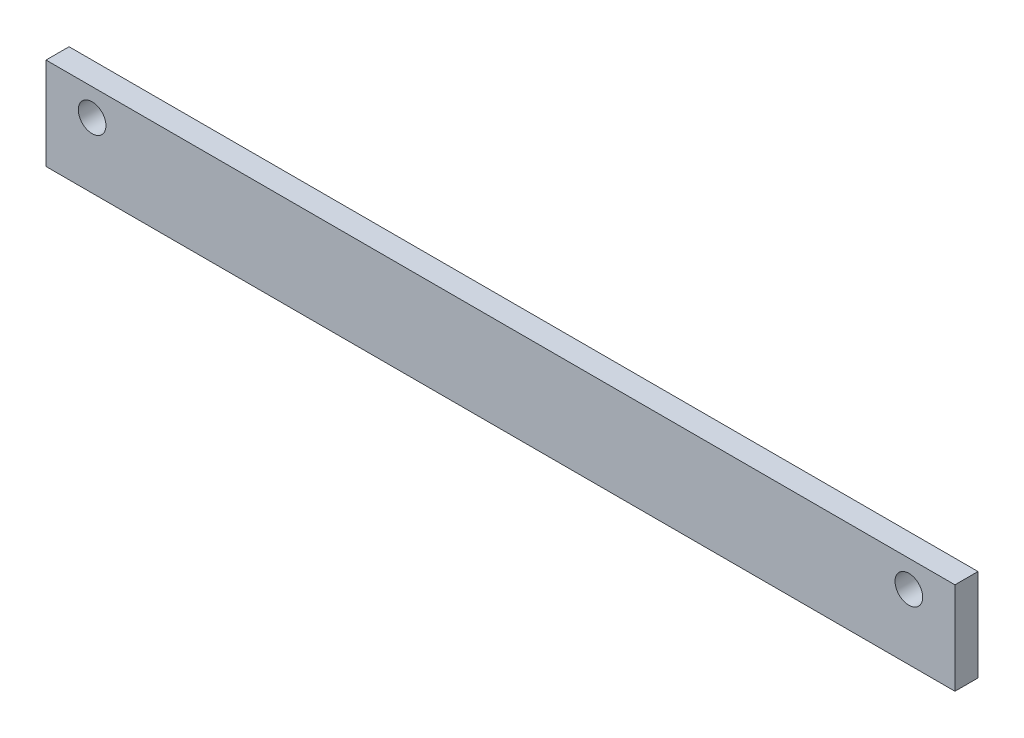
SolidWorks part; units mm, degrees
ref_plane "Piano frontale" through (0, 0, 0) normal (0, 0, 1) x (1, 0, 0)
ref_plane "Piano superiore" through (0, 0, 0) normal (0, 1, 0) x (1, 0, 0)
ref_plane "Piano destro" through (0, 0, 0) normal (1, 0, 0) x (0, 0, -1)
sketch "Schizzo1" plane through (0, 0, 0) normal (0, 0, 1) x (1, 0, 0)
  line L0 (177.1515, 139.7231) -> (177.1515, -15.3961) construction
  line L1 (-20, 99.7231) -> (374.3031, 99.7231)
  line L2 (-20, 99.7231) -> (-20, 139.7231)
  line L3 (-20, 139.7231) -> (374.3031, 139.7231)
  line L4 (374.3031, 99.7231) -> (374.3031, 139.7231)
  circle A1 centre (0, 128.0564) radius 6
  circle A2 centre (0, 128.0564) radius 6 construction
  circle A3 centre (354.3031, 128.0564) radius 6
  point P5 (177.1515, 139.7231)
  dimension "D1" = 40
extrude "Estrusione-Estrusione1" add sketch "Schizzo1" along normal mid plane 10
